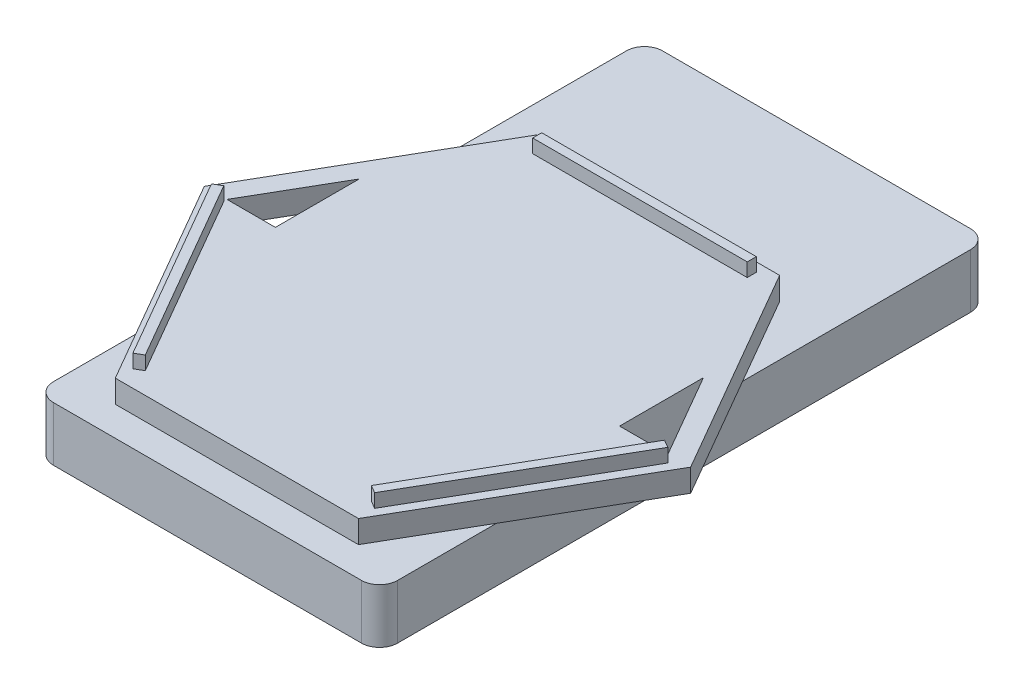
SolidWorks part; units mm, degrees
ref_plane "Plano frontal" through (0, 0, 0) normal (0, 0, 1) x (1, 0, 0)
ref_plane "Plano superior" through (0, 0, 0) normal (0, 1, 0) x (1, 0, 0)
ref_plane "Plano direito" through (0, 0, 0) normal (1, 0, 0) x (0, 0, -1)
sketch "Esboço1" plane through (0, 0, 0) normal (0, 1, 0) x (1, 0, 0)
  line L7 (53.6936, 0) -> (26.8468, 46.5)
  line L8 (26.8468, 46.5) -> (-26.8468, 46.5)
  line L9 (-26.8468, 46.5) -> (-53.6936, 0)
  line L10 (-53.6936, 0) -> (-26.8468, -46.5)
  line L11 (-26.8468, -46.5) -> (26.8468, -46.5)
  line L12 (26.8468, -46.5) -> (53.6936, 0)
  circle A1 centre (0, 0) radius 46.5 construction
extrude "Ressalto-extrusão1" add sketch "Esboço1" along normal blind 3
sketch "Esboço2" plane through (0, 3, 0) normal (0, 1, 0) x (1, 0, 0)
  line L2 (23.6921, 44.5) -> (-23.6921, 44.5)
  line L4 (-50.3842, -1.7321) -> (-26.6921, -42.7679)
  line L6 (26.6921, -42.7679) -> (50.3842, -1.7321)
  line L8 (-23.6921, 44.5) -> (-23.6921, 42.5)
  line L11 (23.6921, 44.5) -> (23.6921, 42.5)
  line L15 (50.3842, -1.7321) -> (48.6521, -0.7321)
  line L18 (26.6921, -42.7679) -> (24.96, -41.7679)
  line L20 (-48.6521, -0.7321) -> (-24.96, -41.7679)
  line L22 (-26.6921, -42.7679) -> (-24.96, -41.7679)
  line L25 (-50.3842, -1.7321) -> (-48.6521, -0.7321)
  line L36 (24.96, -41.7679) -> (48.6521, -0.7321)
  line L38 (23.6921, 42.5) -> (-23.6921, 42.5)
  line L40 (51.3842, 0) -> (25.6921, 44.5) [skipped]
  line L41 (-25.6921, 44.5) -> (-51.3842, 0) [skipped]
  line L42 (-25.6921, -44.5) -> (25.6921, -44.5) [skipped]
extrude "Ressalto-extrusão2" add sketch "Esboço2" along normal blind 3
sketch "Esboço3" plane through (0, 0, 0) normal (0, -1, 0) x (1, 0, 0)
  line L13 (26.8468, 46.5) -> (-26.8468, 46.5)
  line L14 (-26.8468, 46.5) -> (-53.6936, 0)
  line L15 (-53.6936, 0) -> (-26.8468, -46.5)
  line L16 (-26.8468, -46.5) -> (26.8468, -46.5)
  line L17 (26.8468, -46.5) -> (53.6936, 0)
  line L18 (53.6936, 0) -> (26.8468, 46.5)
  circle A0 centre (0, 0) radius 46.5 construction
extrude "Ressalto-extrusão3" add sketch "Esboço3" along normal blind 2
sketch "Esboço5" plane through (0, -2, 0) normal (0, -1, 0) x (1, 0, 0)
  line L1 (38, 49.0015) -> (38, -77.5)
  line L13 (-34, -81.5) -> (34, -81.5)
  line L15 (-34, 53.0015) -> (34, 53.0015)
  line L17 (-38, 49.0015) -> (-38, -77.5)
  arc A0 (38, 49.0015) -> (34, 53.0015) centre (34, 49.0015) ccw
  arc A1 (-34, 53.0015) -> (-38, 49.0015) centre (-34, 49.0015) ccw
  arc A2 (-38, -77.5) -> (-34, -81.5) centre (-34, -77.5) ccw
  arc A3 (34, -81.5) -> (38, -77.5) centre (34, -77.5) ccw
extrude "Ressalto-extrusão5" add sketch "Esboço5" along normal blind 12
sketch "Esboço7" plane through (0, 0, -81.5) normal (0, 0, -1) x (-1, 0, 0)
  line L6 (-34.2, -3) -> (34.2, -3)
  line L8 (-34.2, -3) -> (-34.2, -12.3)
  line L9 (34.2, -3) -> (34.2, -12.3)
  line L10 (31.2, -12.3) -> (34.2, -12.3)
  line L11 (-31.2, -12.3) -> (-34.2, -12.3)
  line L17 (-31.2, -26.2504) -> (31.2, -23.2814)
  line L18 (-31.2, -12.3) -> (-31.2, -26.2504)
  line L19 (31.2, -12.3) -> (31.2, -23.2814)
extrude "Corte-extrusão1" cut sketch "Esboço7" against normal blind 131
sketch "Esboço8" plane through (0, -2, 0) normal (0, -1, 0) x (1, 0, 0)
  line L6 (-48.6936, 0) -> (-38, 0)
  line L7 (38, 0) -> (48.6936, 0)
  line L8 (-48.6936, 0) -> (-38, -18.5218)
  line L10 (38, -18.5218) -> (48.6936, 0)
  line L12 (-38, 0) -> (-38, -18.5218)
  line L13 (38, 0) -> (38, -18.5218)
extrude "Corte-extrusão3" cut sketch "Esboço8" against normal blind 10
